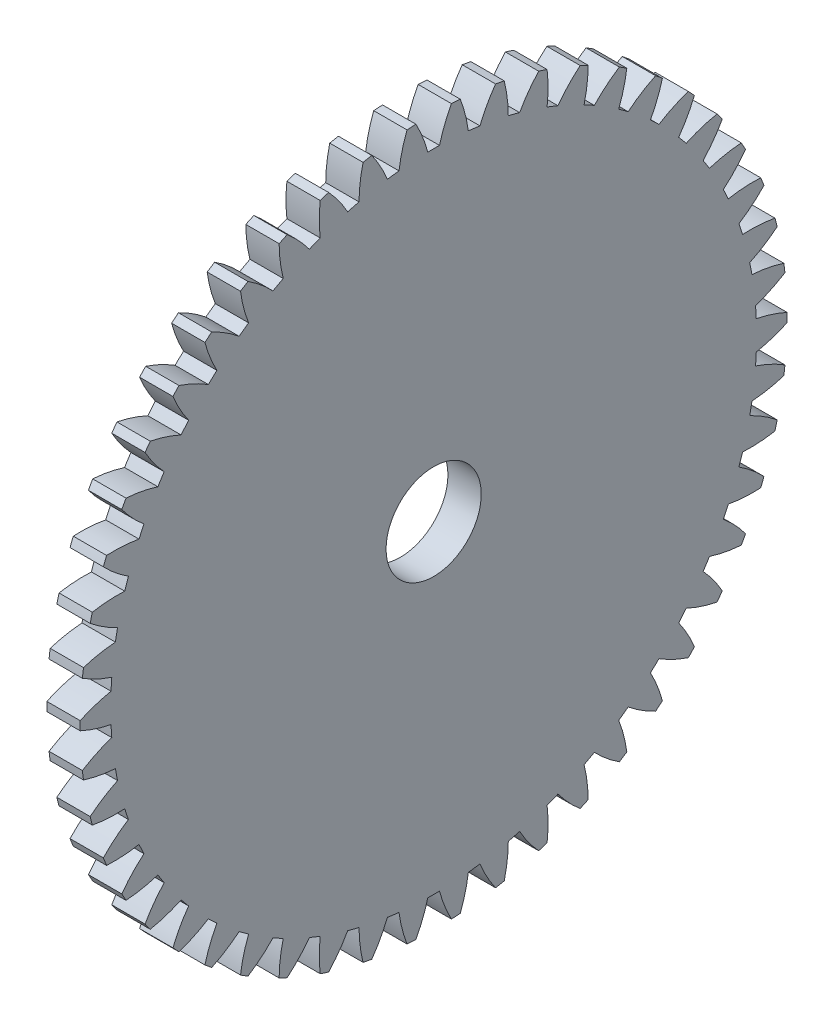
SolidWorks part; units mm, degrees
ref_plane "Plane1" through (0, 0, 0) normal (0, 0, 1) x (1, 0, 0)
ref_plane "Plane2" through (0, 0, 0) normal (0, 1, 0) x (1, 0, 0)
ref_plane "Plane3" through (0, 0, 0) normal (1, 0, 0) x (0, 0, -1)
other "Configuration Table"
sketch "HoldingSke" plane through (0, 0, 0) normal (0, 1, 0) x (1, 0, 0)
  line L0 (0, 0) -> (0.3214, -0.383)
  line L1 (-15, 0) -> (100, 0) construction
  line L2 (0, 0) -> (-2.1039, 2.3779)
  line L3 (0, 0) -> (-11.863, 4.5341)
  line L4 (0, 0) -> (5.5511, 6.6156)
  line L5 (0, 0) -> (-46.8476, -17.4728)
  line L6 (0, 0) -> (-4.0619, -2.7406)
  line L7 (-2.1039, 2.3779) -> (8.6586, 51.2059)
  line L8 (-76.2, 54.61) -> (-73.9, 54.61)
  line L9 (-71.009, 38.7566) -> (-53.1078, 45.2721)
  line L10 (-76.2, 71.12) -> (104.1128, 71.12)
  line L11 (0, 0) -> (-4.9, 0)
  line L12 (-76.2, 101.6) -> (-76.133, 101.6)
  line L13 (24.9733, 27.94) -> (52.9518, 28.4284)
  line L14 (24.9733, 27.94) -> (24.9743, 27.94)
  line L15 (24.9733, 27.94) -> (100.4006, 29.5858)
  line L16 (-63.627, -2) -> (-12.827, -2)
  circle A0 centre (0, 0) radius 7
  circle A1 centre (0, 0) radius 37.5
  circle A2 centre (0, 0) radius 37.5
  circle A3 centre (0, 0) radius 7
  dimension "Hub_dia" = 75
  dimension "Pitch" = 0.5
  dimension "Overall_len" = 50
  dimension "Thickness" = 4.9
  dimension "OAL" = 50.0001
  dimension "Ap" = 20
  dimension "H" = 19.05
  dimension "Pitch_radius" = 180.3128
  dimension "Width" = 4.9
  dimension "Backlash" = 0.067
  dimension "Addendum_fac" = 1
  dimension "Dedendum_fac" = 1.25
  dimension "Clearance_fac" = 0.25
  dimension "Dedendum_add" = 0.001
  dimension "Module" = 2
sketch "BasProSke" plane through (0, 0, 0) normal (0, 1, 0) x (1, 0, 0)
  line L0 (-10, 0) -> (60, 0) construction
  line L1 (0, 0) -> (0, 52)
  line L2 (0, 0) -> (4.9, 0)
  line L3 (4.9, 0) -> (4.9, 52)
  line L4 (4.9, 52) -> (0, 52)
  dimension "Thickness" = 4.9
revolve "Base-Revolve" add sketch "BasProSke" angle 360 about L0
sketch "TooCutSke" plane through (0, 0, 0) normal (1, 0, 0) x (0, 0, -1)
  line L1 (0, 0) -> (0, 107) construction
  line L2 (0, 0) -> (-1.6878, 49.9715) construction
  line L3 (0, 0) -> (-6.2764, 99.7605) construction
  line L4 (-1.6878, 49.9715) -> (-3.1382, 49.8803) construction
  arc A0 (0.8606, 47.4912) -> (-0.8606, 47.4912) centre (0, 0) ccw
  arc A1 (2.629, 51.9589) -> (-2.629, 51.9589) centre (0, 0) ccw
  circle A2 centre (0, 0) radius 50 construction
  circle A3 centre (0, 0) radius 46.9846 construction
  arc A4 (-0.8606, 47.4912) -> (-2.629, 51.9589) centre (-20.2064, 42.4176) ccw
  arc A5 (2.629, 51.9589) -> (0.8606, 47.4912) centre (20.2064, 42.4176) ccw
  dimension "Half_CT" = 1.4533
extrude "ToothCut" cut sketch "TooCutSke" along normal through all
fillet "Breaks" [suppressed] radius 0.04
fillet "RootFillets" [suppressed] radius 0.501
pattern_circular "TeethCuts" count 50 every 7.2 about axis through (-10, 0, 0) along (1, 0, 0) of "ToothCut", "RootFillets", "Breaks"
sketch "HubNeaOneSke" plane through (0, 0, 0) normal (-1, 0, 0) x (0, 0, 1)
  circle A0 centre (0, 0) radius 37.5
extrude "HubNearOne" [suppressed] add sketch "HubNeaOneSke" along normal blind 45.1001
sketch "HubNeaBotSke" plane through (0, 0, 0) normal (-1, 0, 0) x (0, 0, 1)
  circle A0 centre (0, 0) radius 37.5
extrude "HubNearBoth" [suppressed] add sketch "HubNeaBotSke" along normal blind 22.55
ref_plane "FarPln" through (4.9, 0, 0) normal (1, 0, 0) x (0, 0, -1)
sketch "HubFarSke" plane through (4.9, 0, 0) normal (1, 0, 0) x (0, 0, -1)
  circle A0 centre (0, 0) radius 37.5
extrude "HubFar" [suppressed] add sketch "HubFarSke" along normal blind 22.55
sketch "BorSke" plane through (0, 0, 0) normal (1, 0, 0) x (0, 0, -1)
  circle A0 centre (0, 0) radius 7
extrude "Bore" cut sketch "BorSke" along normal mid plane 100.0001
sketch "KeySke" plane through (0, 0, 0) normal (1, 0, 0) x (0, 0, -1)
  line L0 (-2.5, 0) -> (-2.5, 9.3)
  line L1 (-2.5, 9.3) -> (2.5, 9.3)
  line L2 (2.5, 9.3) -> (2.5, 0)
  line L3 (0, 0) -> (0, 34) construction
  line L4 (-2.5, 0) -> (2.5, 0)
extrude "Keyway" [suppressed] cut sketch "KeySke" along normal mid plane 100.0001
pattern_circular "Keyway2" [suppressed] count 2 every 90 about axis through (-10, 0, 0) along (1, 0, 0)
equation "' \"Module@HoldingSke\" = 6.35"
equation "' \"Num_teeth@HoldingSke\" = 12"
equation "' \"Ap@HoldingSke\" =  20"
equation "' \"Ap@HoldingSke\" = 20"
equation "' \"Width@HoldingSke\" = 0.5 * 25.4"
equation "' \"Hub_dia@HoldingSke\"= 1 * 25.4"
equation "' \"Hub_dia@HoldingSke\" = 1 * 25.4"
equation "' \"Overall_len@HoldingSke\" = 1.0 * 25.4"
equation "' \"Bore@HoldingSke\" = 0.75 * 25.4"
equation "' \"T_dim@HoldingSke\" = 0.1 * 25.4"
equation "' \"Width@KeySke\" = 0.25 * 25.4"
equation "' \"Show_teeth@HoldingSke\" = 13"
equation "' \"Backlash@HoldingSke\" = 0.009 * 25.4"
equation "' \"Addendum_fac@HoldingSke\" = 1.0"
equation "' \"Dedendum_fac@HoldingSke\" = 1.25"
equation "' \"Dedendum_add@HoldingSke\" = 0.00005 * 25.4"
equation "' \"Clearance_fac@HoldingSke\" = 0.25"
equation "\"Pitch@HoldingSke\" = 1 / \"Module@HoldingSke\""
equation "\"Overcut_dia@TooCutSke\" = (\"Num_teeth@HoldingSke\" + 2 * \"Addendum_fac@HoldingSke\") / \"Pitch@HoldingSke\" + 0.002 * 25.4"
equation "\"Pitch_dia@TooCutSke\" = \"Num_teeth@HoldingSke\" / \"Pitch@HoldingSke\""
equation "\"Base_dia@TooCutSke\" = \"Num_teeth@HoldingSke\" / \"Pitch@HoldingSke\" * cos((\"Ap@HoldingSke\"  * 3.14159265 / 180))"
equation "\"Root_dia@TooCutSke\" = (\"Num_teeth@HoldingSke\" + 2) / \"Pitch@HoldingSke\" - 2 * (\"Addendum_fac@HoldingSke\" + \"Dedendum_fac@HoldingSke\") / \"Pitch@HoldingSke\" - \"Dedendum_add@HoldingSke\" * 2"
equation "\"Half_ang@TooCutSke\" = 180 / \"Num_teeth@HoldingSke\""
equation "\"Half_CT@TooCutSke\" = \"Num_teeth@HoldingSke\" / \"Pitch@HoldingSke\" * sin((3.14159265 / 2 / \"Num_teeth@HoldingSke\")) / 2 - 7 * \"Backlash@HoldingSke\" / 4"
equation "\"Flank_rad@TooCutSke\" = \"Num_teeth@HoldingSke\" / \"Pitch@HoldingSke\" / 5"
equation "\"Radius@RootFillets\" = \"Clearance_fac@HoldingSke\" / \"Pitch@HoldingSke\" + \"Dedendum_add@HoldingSke\""
equation "\"Break_rad@Breaks\" = 0.02 / \"Pitch@HoldingSke\""
equation "\"Thickness@HoldingSke\" = \"Width@HoldingSke\""
equation "\"OAL@HoldingSke\" = \"Thickness@HoldingSke\""
equation "\"MHD@HoldingSke\" = (\"Num_teeth@HoldingSke\" + 2) / \"Pitch@HoldingSke\" - 2 * (\"Addendum_fac@HoldingSke\" + \"Dedendum_fac@HoldingSke\")  / \"Pitch@HoldingSke\" - \"Dedendum_add@HoldingSke\" * 2"
equation "\"MBD@HoldingSke\" = (\"Num_teeth@HoldingSke\" + 2) / \"Pitch@HoldingSke\" - 2 * (\"Addendum_fac@HoldingSke\" + \"Dedendum_fac@HoldingSke\")  / \"Pitch@HoldingSke\" - \"Dedendum_add@HoldingSke\" * 2 - 0.002 * 25.4"
equation "\"MHD@HoldingSke\" = ((sgn( \"MHD@HoldingSke\" - \"Hub_dia@HoldingSke\" )-1)*( \"MHD@HoldingSke\" - \"Hub_dia@HoldingSke\" ))/-2+ \"Hub_dia@HoldingSke\""
equation "\"MBD@HoldingSke\" = ((sgn( \"MBD@HoldingSke\" - \"Bore@HoldingSke\" )-1)*( \"MBD@HoldingSke\" - \"Bore@HoldingSke\" ))/-2+ \"Bore@HoldingSke\""
equation "\"OAL@HoldingSke\" = ((sgn( \"OAL@HoldingSke\" - \"Overall_len@HoldingSke\" )+1)*( \"OAL@HoldingSke\" - \"Overall_len@HoldingSke\" ))/2 + \"Overall_len@HoldingSke\" + 0.000002 * 25.4"
equation "\"Num_teeth@TeethCuts\" = int( \"Show_teeth@HoldingSke\" ) + 1"
equation "\"Num_teeth@TeethCuts\" = ((sgn( \"Num_teeth@TeethCuts\" - \"Num_teeth@HoldingSke\" )-1)*( \"Num_teeth@TeethCuts\" - \"Num_teeth@HoldingSke\" ))/-2+ \"Num_teeth@HoldingSke\""
equation "\"Num_teeth@TeethCuts\" = ((sgn( \"Num_teeth@TeethCuts\" - 2.0)+1)*( \"Num_teeth@TeethCuts\" - 2.0))/2 +2.0"
equation "\"Angle@TeethCuts\" = 360.0 / \"Num_teeth@HoldingSke\""
equation "\"Diameter@BasProSke\" = (\"Num_teeth@HoldingSke\" + 2 * \"Addendum_fac@HoldingSke\") / \"Pitch@HoldingSke\""
equation "\"Thickness@BasProSke\"  = \"Thickness@HoldingSke\""
equation "' \"Fillet_rad@BasProSke\" =  \"Thickness@HoldingSke\" * 0.05"
equation "' \"Fillet_rad@BasProSke\" = \"Thickness@HoldingSke\" * 0.05"
equation "\"MHD@HoldingSke\" = ((sgn( \"MHD@HoldingSke\" - \"Root_dia@TooCutSke\" )-1)*( \"MHD@HoldingSke\" - \"Root_dia@TooCutSke\" ))/-2+ \"Root_dia@TooCutSke\""
equation "\"Diameter@HubNeaOneSke\" = \"MHD@HoldingSke\""
equation "\"Length@HubNearOne\" = \"OAL@HoldingSke\" - \"Thickness@BasProSke\""
equation "\"Diameter@HubNeaBotSke\" = \"MHD@HoldingSke\""
equation "\"Length@HubNearBoth\" = ( \"OAL@HoldingSke\" - \"Thickness@BasProSke\" ) / 2.0"
equation "\"Thickness@FarPln\" = \"Thickness@BasProSke\""
equation "\"Diameter@HubFarSke\" = \"MHD@HoldingSke\""
equation "\"Length@HubFar\" = ( \"OAL@HoldingSke\" - \"Thickness@BasProSke\" ) / 2.0"
equation "\"Diameter@BorSke\" = \"MBD@HoldingSke\""
equation "\"D1@Bore\" = \"OAL@HoldingSke\" * 2.0"
equation "\"D1@Keyway\" = \"OAL@HoldingSke\" * 2.0"
equation "\"Offset@KeySke\" = \"T_dim@HoldingSke\" + \"MBD@HoldingSke\" / 2.0"
